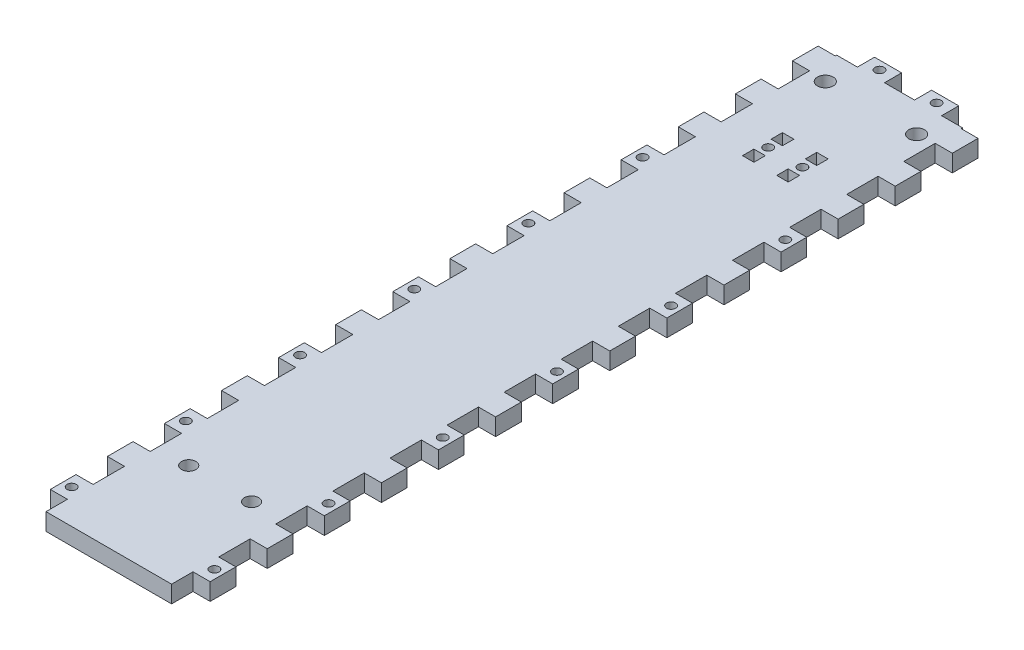
SolidWorks part; units mm, degrees
ref_plane "Plan de face" through (0, 0, 0) normal (0, 0, 1) x (1, 0, 0)
ref_plane "Plan de dessus" through (0, 0, 0) normal (0, 1, 0) x (1, 0, 0)
ref_plane "Plan de droite" through (0, 0, 0) normal (1, 0, 0) x (0, 0, -1)
sketch "Sketch1" plane through (0, 0, 0) normal (0, 1, 0) x (1, 0, 0)
  line L0 (50, 276.5) -> (50, 267.5)
  line L1 (0, 0) -> (44, 0)
  line L2 (0, 0) -> (0, 277)
  line L3 (0, 277) -> (44, 277)
  line L4 (44, 0) -> (44, 277)
  line L5 (0, 276.5) -> (-6, 276.5)
  line L6 (0, 276.5) -> (0, 267.5)
  line L7 (0, 267.5) -> (-6, 267.5)
  line L8 (-6, 276.5) -> (-6, 267.5)
  line L9 (50, 276.5) -> (44, 276.5)
  line L10 (44, 276.5) -> (44, 267.5)
  line L11 (50, 267.5) -> (44, 267.5)
  line L12 (50, 256.5) -> (50, 247.5)
  line L13 (50, 256.5) -> (44, 256.5)
  line L14 (44, 256.5) -> (44, 247.5)
  line L15 (50, 247.5) -> (44, 247.5)
  line L16 (50, 236.5) -> (50, 227.5)
  line L17 (50, 236.5) -> (44, 236.5)
  line L18 (44, 236.5) -> (44, 227.5)
  line L19 (50, 227.5) -> (44, 227.5)
  line L20 (50, 216.5) -> (50, 207.5)
  line L21 (50, 216.5) -> (44, 216.5)
  line L22 (44, 216.5) -> (44, 207.5)
  line L23 (50, 207.5) -> (44, 207.5)
  line L24 (50, 196.5) -> (50, 187.5)
  line L25 (50, 196.5) -> (44, 196.5)
  line L26 (44, 196.5) -> (44, 187.5)
  line L27 (50, 187.5) -> (44, 187.5)
  line L28 (50, 176.5) -> (50, 167.5)
  line L29 (50, 176.5) -> (44, 176.5)
  line L30 (44, 176.5) -> (44, 167.5)
  line L31 (50, 167.5) -> (44, 167.5)
  line L32 (50, 156.5) -> (50, 147.5)
  line L33 (50, 156.5) -> (44, 156.5)
  line L34 (44, 156.5) -> (44, 147.5)
  line L35 (50, 147.5) -> (44, 147.5)
  line L36 (50, 136.5) -> (50, 127.5)
  line L37 (50, 136.5) -> (44, 136.5)
  line L38 (44, 136.5) -> (44, 127.5)
  line L39 (50, 127.5) -> (44, 127.5)
  line L40 (50, 116.5) -> (50, 107.5)
  line L41 (50, 116.5) -> (44, 116.5)
  line L42 (44, 116.5) -> (44, 107.5)
  line L43 (50, 107.5) -> (44, 107.5)
  line L44 (50, 96.5) -> (50, 87.5)
  line L45 (50, 96.5) -> (44, 96.5)
  line L46 (44, 96.5) -> (44, 87.5)
  line L47 (50, 87.5) -> (44, 87.5)
  line L48 (50, 76.5) -> (50, 67.5)
  line L49 (50, 76.5) -> (44, 76.5)
  line L50 (44, 76.5) -> (44, 67.5)
  line L51 (50, 67.5) -> (44, 67.5)
  line L52 (50, 56.5) -> (50, 47.5)
  line L53 (50, 56.5) -> (44, 56.5)
  line L54 (44, 56.5) -> (44, 47.5)
  line L55 (50, 47.5) -> (44, 47.5)
  line L56 (50, 36.5) -> (50, 27.5)
  line L57 (50, 36.5) -> (44, 36.5)
  line L58 (44, 36.5) -> (44, 27.5)
  line L59 (50, 27.5) -> (44, 27.5)
  line L60 (50, 16.5) -> (50, 7.5)
  line L61 (50, 16.5) -> (44, 16.5)
  line L62 (44, 16.5) -> (44, 7.5)
  line L63 (50, 7.5) -> (44, 7.5)
  line L64 (0, 256.5) -> (0, 247.5)
  line L65 (0, 256.5) -> (-6, 256.5)
  line L66 (-6, 256.5) -> (-6, 247.5)
  line L67 (0, 247.5) -> (-6, 247.5)
  line L68 (0, 236.5) -> (0, 227.5)
  line L69 (0, 236.5) -> (-6, 236.5)
  line L70 (-6, 236.5) -> (-6, 227.5)
  line L71 (0, 227.5) -> (-6, 227.5)
  line L72 (0, 216.5) -> (0, 207.5)
  line L73 (0, 216.5) -> (-6, 216.5)
  line L74 (-6, 216.5) -> (-6, 207.5)
  line L75 (0, 207.5) -> (-6, 207.5)
  line L76 (0, 196.5) -> (0, 187.5)
  line L77 (0, 196.5) -> (-6, 196.5)
  line L78 (-6, 196.5) -> (-6, 187.5)
  line L79 (0, 187.5) -> (-6, 187.5)
  line L80 (0, 176.5) -> (0, 167.5)
  line L81 (0, 176.5) -> (-6, 176.5)
  line L82 (-6, 176.5) -> (-6, 167.5)
  line L83 (0, 167.5) -> (-6, 167.5)
  line L84 (0, 156.5) -> (0, 147.5)
  line L85 (0, 156.5) -> (-6, 156.5)
  line L86 (-6, 156.5) -> (-6, 147.5)
  line L87 (0, 147.5) -> (-6, 147.5)
  line L88 (0, 136.5) -> (0, 127.5)
  line L89 (0, 136.5) -> (-6, 136.5)
  line L90 (-6, 136.5) -> (-6, 127.5)
  line L91 (0, 127.5) -> (-6, 127.5)
  line L92 (0, 116.5) -> (0, 107.5)
  line L93 (0, 116.5) -> (-6, 116.5)
  line L94 (-6, 116.5) -> (-6, 107.5)
  line L95 (0, 107.5) -> (-6, 107.5)
  line L96 (0, 96.5) -> (0, 87.5)
  line L97 (0, 96.5) -> (-6, 96.5)
  line L98 (-6, 96.5) -> (-6, 87.5)
  line L99 (0, 87.5) -> (-6, 87.5)
  line L100 (0, 76.5) -> (0, 67.5)
  line L101 (0, 76.5) -> (-6, 76.5)
  line L102 (-6, 76.5) -> (-6, 67.5)
  line L103 (0, 67.5) -> (-6, 67.5)
  line L104 (0, 56.5) -> (0, 47.5)
  line L105 (0, 56.5) -> (-6, 56.5)
  line L106 (-6, 56.5) -> (-6, 47.5)
  line L107 (0, 47.5) -> (-6, 47.5)
  line L108 (0, 36.5) -> (0, 27.5)
  line L109 (0, 36.5) -> (-6, 36.5)
  line L110 (-6, 36.5) -> (-6, 27.5)
  line L111 (0, 27.5) -> (-6, 27.5)
  line L112 (0, 16.5) -> (0, 7.5)
  line L113 (0, 16.5) -> (-6, 16.5)
  line L114 (-6, 16.5) -> (-6, 7.5)
  line L115 (0, 7.5) -> (-6, 7.5)
  line L117 (7.25, 277) -> (16.75, 277)
  line L118 (7.25, 277) -> (7.25, 283)
  line L119 (7.25, 283) -> (16.75, 283)
  line L120 (16.75, 277) -> (16.75, 283)
  line L121 (36.75, 277) -> (27.25, 277)
  line L122 (36.75, 277) -> (36.75, 283)
  line L123 (36.75, 283) -> (27.25, 283)
  line L124 (27.25, 277) -> (27.25, 283)
  dimension "D1" = 277
  dimension "D2" = 44
  dimension "D3" = 9
  dimension "D4" = 6
  dimension "D5" = 0.5
  dimension "D8" = 9.5
  dimension "D9" = 6
  dimension "D10" = 7.25
  dimension "D11" = 9.5
  dimension "D12" = 6
  dimension "D13" = 7.25
  dimension "D6" = 2
  dimension "D7" = 14
extrude "Boss-Extrude1" add sketch "Sketch1" along normal blind 6 contours L1 L4 L3 L2 | L115 L2 L113 L114 | L111 L2 L109 L110 | L107 L2 L105 L106 | L103 L2 L101 L102 | L99 L2 L97 L98 | L95 L2 L93 L94 | L91 L2 L89 L90 | L87 L2 L85 L86 | L83 L2 L81 L82 | L79 L2 L77 L78 | L75 L2 L73 L74 | L71 L2 L69 L70 | L67 L2 L65 L66 | L5 L8 L7 L2 | L3 L120 L119 L118 | L124 L3 L122 L123 | L11 L0 L9 L4 | L15 L12 L13 L4 | L19 L16 L17 L4 | L23 L20 L21 L4 | L27 L24 L25 L4 | L31 L28 L29 L4 | L35 L32 L33 L4 | L39 L36 L37 L4 | L43 L40 L41 L4 | L47 L44 L45 L4 | L51 L48 L49 L4 | L55 L52 L53 L4 | L59 L56 L57 L4 | L63 L60 L61 L4
sketch "Sketch2" plane through (0, 6, 0) normal (0, 1, 0) x (1, 0, 0)
  line L0 (16.75, 277) -> (27.25, 277) construction
  circle A0 centre (6, 267) radius 2.75
  circle A1 centre (38, 267) radius 2.75
  point P6 (22, 277)
  dimension "D1" = 5.5
  dimension "D2" = 5.5
  dimension "D3" = 32
  dimension "D4" = 10
  dimension "D5" = 16
extrude "Cut-Extrude1" cut sketch "Sketch2" against normal through all both and the other way through all
sketch "Sketch3" plane through (0, 6, 0) normal (0, 1, 0) x (1, 0, 0)
  line L0 (14, 244) -> (18, 244)
  line L1 (14, 244) -> (14, 240)
  line L2 (14, 240) -> (18, 240)
  line L3 (18, 244) -> (18, 240)
  line L4 (14, 234) -> (18, 234)
  line L5 (14, 234) -> (14, 230)
  line L6 (14, 230) -> (18, 230)
  line L7 (18, 234) -> (18, 230)
  line L8 (26, 244) -> (30, 244)
  line L9 (26, 244) -> (26, 240)
  line L10 (26, 240) -> (30, 240)
  line L11 (30, 244) -> (30, 240)
  line L12 (26, 234) -> (30, 234)
  line L13 (26, 234) -> (26, 230)
  line L14 (26, 230) -> (30, 230)
  line L15 (30, 234) -> (30, 230)
  line L16 (16.75, 277) -> (27.25, 277) construction
  circle A0 centre (16, 237) radius 1.6
  circle A1 centre (28, 237) radius 1.6
  point P20 (16, 240)
  point P21 (28, 240)
  point P24 (22, 277)
  dimension "D12" = 3.2
  dimension "D13" = 3.2
  dimension "D1" = 4
  dimension "D2" = 4
  dimension "D3" = 4
  dimension "D4" = 4
  dimension "D5" = 6
  dimension "D6" = 4
  dimension "D7" = 4
  dimension "D8" = 4
  dimension "D9" = 4
  dimension "D10" = 6
  dimension "D11" = 8
  dimension "D14" = 3
  dimension "D15" = 4
  dimension "D16" = 33
extrude "Cut-Extrude2" cut sketch "Sketch3" against normal through all both and the other way through all
sketch "Sketch4" plane through (0, 6, 0) normal (0, 1, 0) x (1, 0, 0)
  line L0 (0, 0) -> (44, 0) construction
  line L1 (22, 0) -> (22, 10.4293) construction
  circle A0 centre (33, 39) radius 2.5
  circle A1 centre (11, 39) radius 2.5
  point P6 (22, 0)
  dimension "D1" = 5
  dimension "D2" = 39
  dimension "D3" = 11
extrude "Cut-Extrude3" cut sketch "Sketch4" against normal through all both and the other way through all
sketch "Sketch5" plane through (0, 6, 0) normal (0, 1, 0) x (1, 0, 0)
  line L0 (0, 16.5) -> (-6, 16.5) construction
  line L1 (-6, 16.5) -> (-6, 7.5) construction
  line L2 (7.25, 283) -> (16.75, 283) construction
  line L3 (36.75, 283) -> (27.25, 283) construction
  line L4 (7.25, 277) -> (7.25, 283) construction
  circle A0 centre (-3, 12) radius 1.6
  circle A1 centre (47, 12) radius 1.6
  circle A2 centre (47, 52) radius 1.6
  circle A3 centre (47, 92) radius 1.6
  circle A4 centre (47, 132) radius 1.6
  circle A5 centre (47, 172) radius 1.6
  circle A6 centre (47, 212) radius 1.6
  circle A7 centre (-3, 52) radius 1.6
  circle A8 centre (-3, 92) radius 1.6
  circle A9 centre (-3, 132) radius 1.6
  circle A10 centre (-3, 172) radius 1.6
  circle A11 centre (-3, 212) radius 1.6
  circle A12 centre (32, 280) radius 1.6
  circle A13 centre (12, 280) radius 1.6
  point P5 (-3, 16.5)
  point P9 (-6, 12)
  point P34 (0, 0)
  point P37 (12, 283)
  point P38 (0, 0)
  point P41 (32, 283)
  point P42 (0, 0)
  point P45 (7.25, 280)
  dimension "D1" = 3.2
  dimension "D4" = 3.2
  dimension "D5" = 3.2
  dimension "D2" = 2
  dimension "D3" = 6
extrude "Cut-Extrude4" cut sketch "Sketch5" against normal through all both and the other way through all
